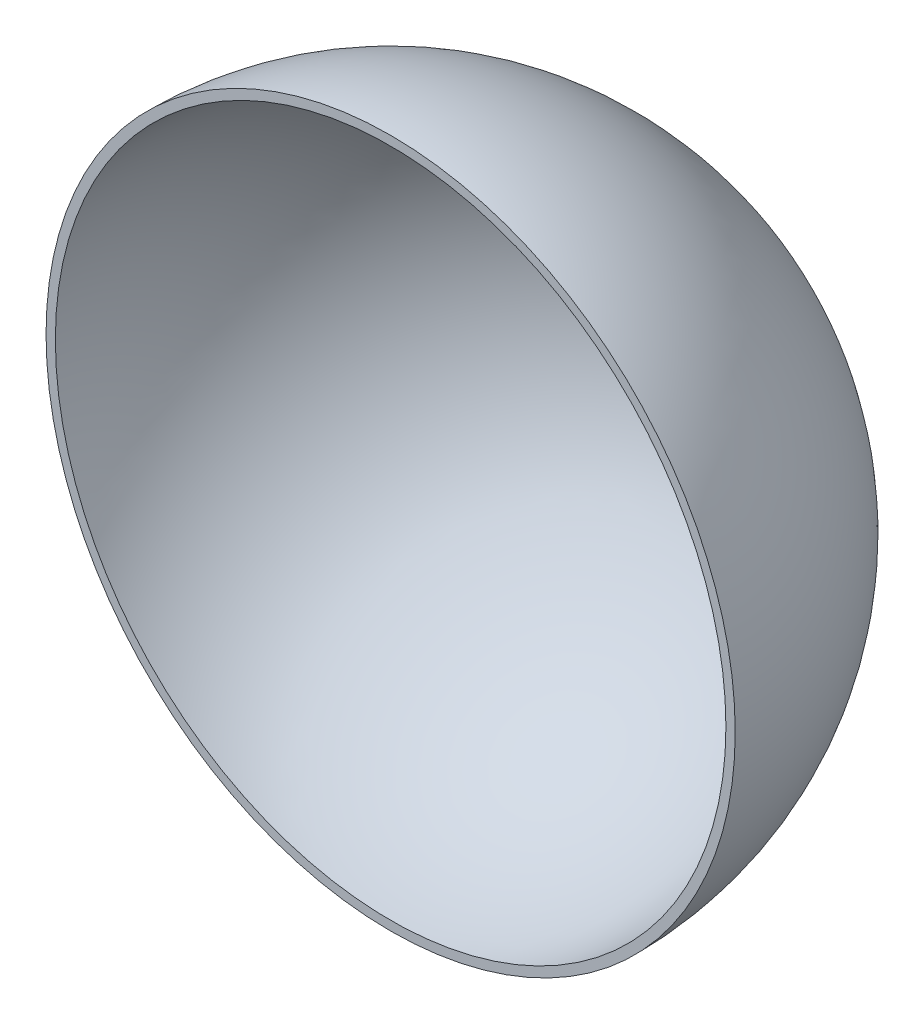
SolidWorks part; units mm, degrees
material "6061-T6 (SS)"
ref_plane "Front Plane" through (0, 0, 0) normal (0, 0, 1) x (1, 0, 0)
ref_plane "Top Plane" through (0, 0, 0) normal (0, 1, 0) x (1, 0, 0)
ref_plane "Right Plane" through (0, 0, 0) normal (1, 0, 0) x (0, 0, -1)
sketch "Sketch1" plane through (0, 0, 0) normal (0, 0, 1) x (1, 0, 0)
  line L0 (0, -228.6) -> (0, 228.6) construction
  line L1 (0, 228.6) -> (0, 234.95)
  line L2 (0, -228.6) -> (0, -234.95)
  arc A0 (0, -228.6) -> (0, 228.6) centre (0, 0) ccw
  arc A1 (0, 234.95) -> (0, -234.95) centre (0, 0) cw
  dimension "D1" = 457.2
  dimension "D2" = 228.6
  dimension "D3" = 6.35
  dimension "D4" = 6.35
revolve "Revolve1" add sketch "Sketch1" angle 180 about L0
ref_plane "Plane1" through (0, 0, -234.95) normal (0, 0, -1) x (-1, 0, 0)
sketch "Sketch2" plane through (0, 0, -234.95) normal (0, 0, -1) x (-1, 0, 0)
  circle A0 centre (0, 0) radius 6.35
  dimension "D1" = 12.7
extrude "Cut-Extrude1" cut sketch "Sketch2" against normal through all
